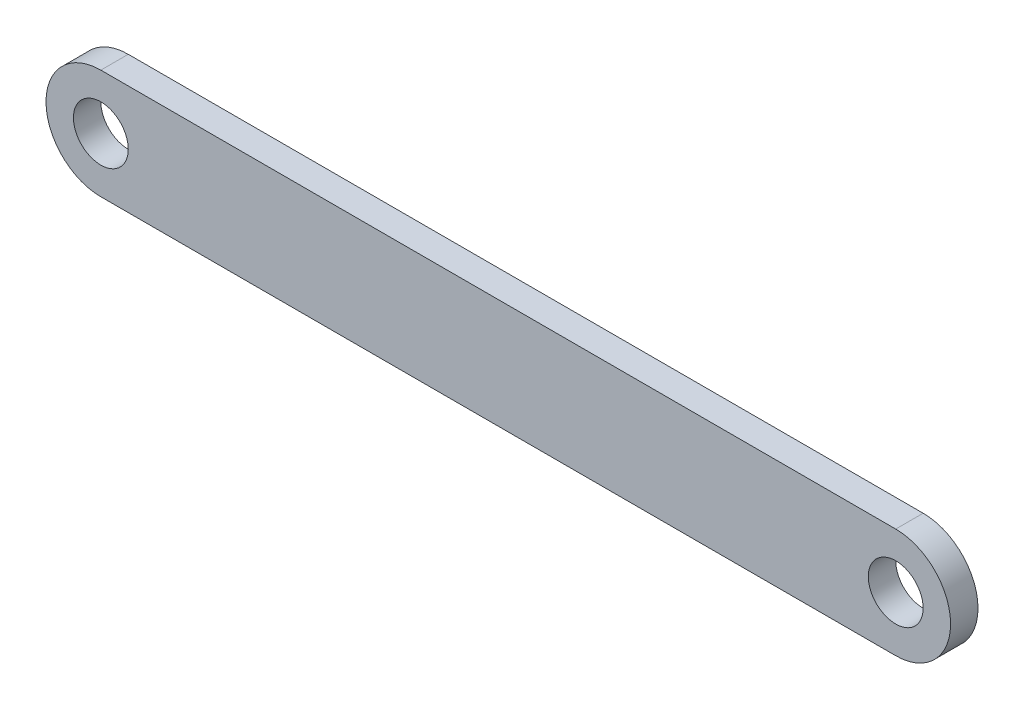
SolidWorks part; units mm, degrees
ref_plane "Спереди" through (0, 0, 0) normal (0, 0, 1) x (1, 0, 0)
ref_plane "Сверху" through (0, 0, 0) normal (0, 1, 0) x (1, 0, 0)
ref_plane "Справа" through (0, 0, 0) normal (1, 0, 0) x (0, 0, -1)
sketch "Sketch1" plane through (0, 0, 0) normal (0, 0, 1) x (1, 0, 0)
  line L0 (0, 0) -> (-28.986, 0)
  line L1 (-28.986, 2) -> (0, 2)
  line L2 (-28.986, -2) -> (0, -2)
  circle A0 centre (0, 0) radius 1
  circle A1 centre (0, 0) radius 2
  circle A2 centre (-28.986, 0) radius 1
  circle A3 centre (-28.986, 0) radius 2
extrude "Extrude1" add sketch "Sketch1" along normal blind 1
